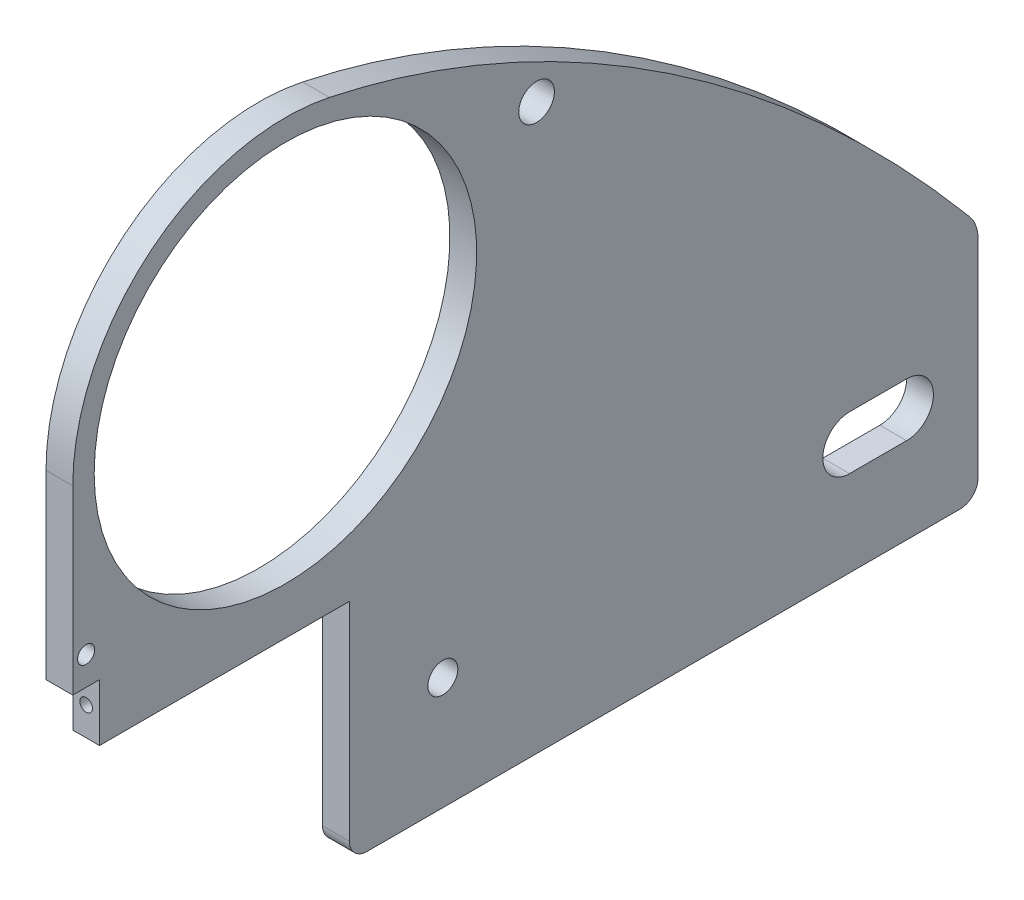
SolidWorks part; units mm, degrees
ref_plane "Front Plane" through (0, 0, 0) normal (0, 0, 1) x (1, 0, 0)
ref_plane "Top Plane" through (0, 0, 0) normal (0, 1, 0) x (1, 0, 0)
ref_plane "Right Plane" through (0, 0, 0) normal (1, 0, 0) x (0, 0, -1)
sketch "Sketch1" plane through (0, 0, 0) normal (1, 0, 0) x (0, 0, -1)
  line L0 (-28.1703, 0) -> (77.3828, 0)
  line L1 (80.5578, 3.175) -> (80.5578, 40.132)
  line L2 (-80.5578, 82.55) -> (-80.5578, 50.292)
  line L4 (-75.7953, 50.292) -> (-75.7953, 40.132)
  line L5 (67.8578, 20.066) -> (57.6978, 20.066) construction
  line L6 (67.8578, 15.3035) -> (57.6978, 15.3035)
  line L7 (-75.7953, 40.132) -> (-31.3453, 40.132)
  line L10 (-31.3453, 40.132) -> (-31.3453, 3.175)
  line L11 (-80.5578, 50.292) -> (-75.7953, 50.292)
  line L12 (67.8578, 24.8285) -> (57.6978, 24.8285)
  arc A0 (67.8578, 15.3035) -> (67.8578, 24.8285) centre (67.8578, 20.066) ccw
  circle A1 centre (-42.7078, 82.55) radius 31.5 construction
  circle A2 centre (67.8578, 20.066) radius 76.2 construction
  circle A3 centre (-78.1765, 55.372) radius 1.524
  arc A4 (57.6978, 24.8285) -> (57.6978, 15.3035) centre (57.6978, 20.066) ccw
  arc A5 (-34.8673, 119.579) -> (-80.5578, 82.55) centre (-42.7078, 82.55) ccw
  arc A6 (-28.1703, 0) -> (-31.3453, 3.175) centre (-28.1703, 3.175) cw
  arc A7 (77.3828, 0) -> (80.5578, 3.175) centre (77.3828, 3.175) ccw
  arc A8 (80.5578, 40.132) -> (79.0734, 44.2123) centre (74.2078, 40.132) ccw
  circle A9 centre (1.9922, 100.457) radius 3.175
  circle A10 centre (1.9922, 100.457) radius 5.5562 construction
  circle A11 centre (-14.6922, 20.066) radius 2.667
  circle A16 centre (-42.7078, 82.55) radius 34.04
  spline S0 degree 3 poles (-34.8673, 119.579) (-0.0583, 112.2086) (41.2638, 89.2986) (79.0734, 44.2123) knots 0 0 0 0 1 1 1 1
  spline S1 degree 3 poles (79.0888, 44.1938) (50.6675, 78.3472) (10.808, 109.6876) (-34.6964, 119.5424) knots 0 0 0 0 1 1 1 1 construction
  point P8 (80.5578, 21.6535)
  point P10 (-31.3453, 21.6535)
  point P13 (62.7778, 20.066)
  point P28 (80.5578, 40.132)
  dimension "D4" = 9.525
  dimension "D7" = 4.7625
  dimension "D8" = 63
  dimension "D9" = 6.35
  dimension "D12" = 3.175
  dimension "D13" = 6.35
  dimension "D14" = 2.54
  dimension "D15" = 152.4
  dimension "D18" = 5.334
  dimension "D19" = 5.08
  dimension "D20" = 82.55
  dimension "D17" = 3.048
  dimension "D24" = 6.35
  dimension "D25" = 11.1125
  dimension "D2" = 40.132
  dimension "D3" = 20.066
  dimension "D5" = 12.7
  dimension "D6" = 44.45
  dimension "D10" = 127
  dimension "D11" = 95.25
  dimension "D21" = 10.16
  dimension "D22" = 10.16
  dimension "D16" = 2.3813
  dimension "D23" = 60.325
extrude "Boss-Extrude1" add sketch "Sketch1" along normal blind 4.7625
sketch "Sketch2" plane through (0, 0, 75.7953) normal (0, 0, 1) x (1, 0, 0)
  line L0 (0, 50.292) -> (0, 40.132) construction
  line L1 (4.7625, 40.132) -> (0, 40.132) construction
  circle A0 centre (2.3813, 45.212) radius 1.1303
  point P4 (0, 45.212)
  point P7 (2.3813, 40.132)
  dimension "D1" = 2.2606
extrude "Cut-Extrude1" cut sketch "Sketch2" against normal blind 6.35
